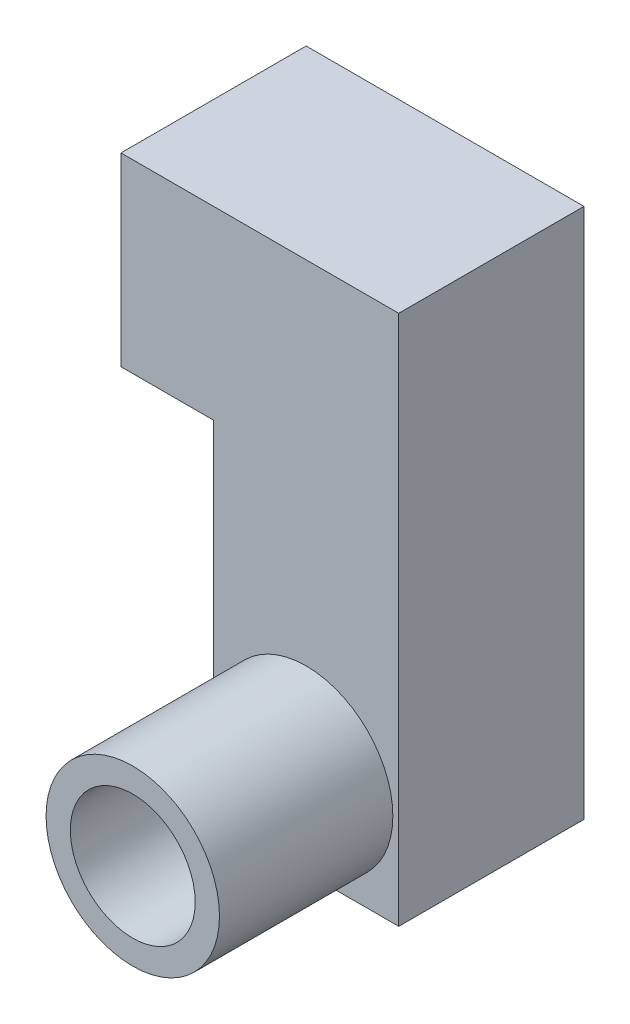
SolidWorks part; units mm, degrees
ref_plane "Front Plane" through (0, 0, 0) normal (0, 0, 1) x (1, 0, 0)
ref_plane "Top Plane" through (0, 0, 0) normal (0, 1, 0) x (1, 0, 0)
ref_plane "Right Plane" through (0, 0, 0) normal (1, 0, 0) x (0, 0, -1)
sketch "Sketch2" plane through (0, 0, 0) normal (0, 0, 1) x (1, 0, 0)
  line L0 (0, -13.35) -> (13.35, -13.35)
  line L1 (0, -55) -> (0, 55) construction
  line L2 (13.35, -13.35) -> (13.35, 63.2)
  line L3 (13.35, 63.2) -> (-26.7, 63.2)
  line L4 (-26.7, 63.2) -> (-26.7, 36.5)
  line L5 (-26.7, 36.5) -> (-13.35, 36.5)
  line L6 (-13.35, 36.5) -> (-13.35, -13.35)
  line L7 (-13.35, -13.35) -> (0, -13.35)
  dimension "D1" = 13.35
  dimension "D2" = 26.7
  dimension "D3" = 13.35
  dimension "D4" = 26.7
  dimension "D5" = 13.35
  dimension "D6" = 36.5
extrude "Boss-Extrude1" add sketch "Sketch2" against normal mid plane 26.7
sketch "Sketch3" plane through (0, 0, 13.35) normal (0, 0, 1) x (1, 0, 0)
  circle A0 centre (0, 0) radius 9
extrude "Cut-Extrude1" cut sketch "Sketch3" against normal blind 23
sketch "Sketch4" plane through (-26.7, 0, 0) normal (-1, 0, 0) x (0, 0, 1)
  line L0 (0, -22.0275) -> (0, 22.0275) construction
  line L1 (-13.35, 36.5) -> (13.35, 36.5) construction
  circle A0 centre (0, 49.85) radius 11.5
  dimension "D1" = 23
  dimension "D2" = 13.35
extrude "Cut-Extrude3" cut sketch "Sketch4" against normal blind 35.7
sketch "Sketch7" plane through (0, 0, 0) normal (0, 1, 0) x (1, 0, 0)
  circle A0 centre (0, 0) radius 9
extrude "Cut-Extrude9" cut sketch "Sketch7" along normal blind 49.85
sketch "Sketch8" plane through (0, 0, 13.35) normal (0, 0, 1) x (1, 0, 0)
  circle A0 centre (0, 0) radius 12.5
  circle A1 centre (0, 0) radius 9
extrude "Boss-Extrude2" add sketch "Sketch8" along normal blind 25
